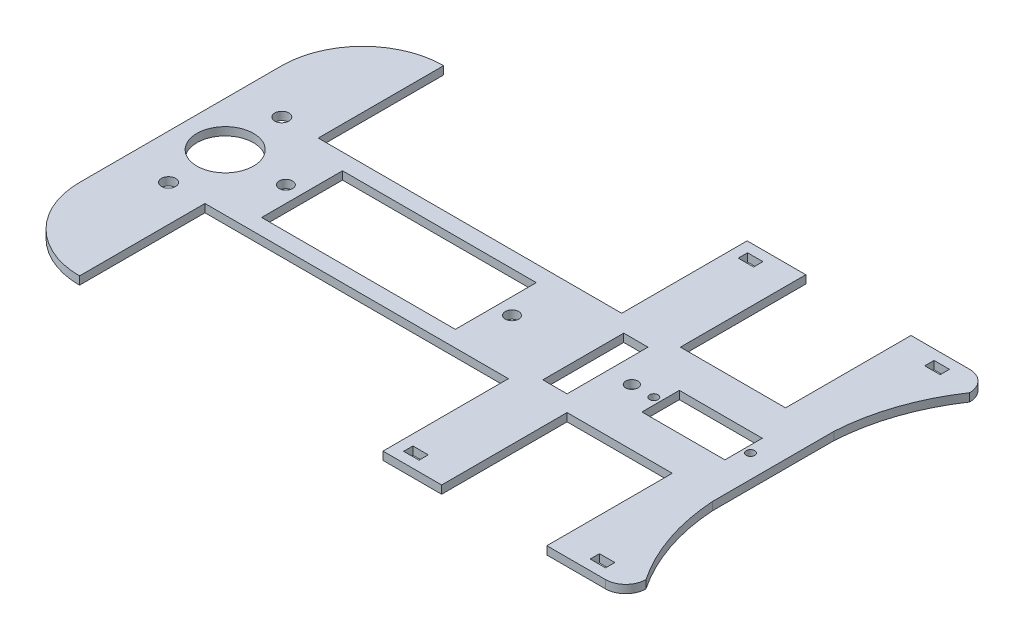
SolidWorks part; units mm, degrees
ref_plane "Front" through (0, 0, 0) normal (0, 0, 1) x (1, 0, 0)
ref_plane "Top" through (0, 0, 0) normal (0, 1, 0) x (1, 0, 0)
ref_plane "Right" through (0, 0, 0) normal (1, 0, 0) x (0, 0, -1)
sketch "Croquis1" plane through (0, 0, 0) normal (0, 1, 0) x (1, 0, 0)
  line L0 (-677.3338, 0) -> (33189.3559, 0) construction
  line L1 (0, -677.3338) -> (0, 33189.3559) construction
  line L2 (-58.4622, -14) -> (-58.4622, 14) construction
  line L3 (-49.4622, 45) -> (-49.4622, 14)
  line L4 (-69.4622, -25) -> (-69.4622, 25)
  line L5 (-49.4622, 14) -> (25.5378, 14)
  line L6 (-677.3338, -25) -> (33189.3559, -25) construction
  line L7 (-677.3338, 25) -> (33189.3559, 25) construction
  line L8 (80.5378, -45) -> (66.0378, -45)
  line L9 (49.1653, -4.625) -> (69.6653, -4.625)
  line L10 (49.1653, -4.625) -> (49.1653, 4.625)
  line L11 (30.0378, -962) -> (30.0378, 49038) construction
  line L12 (28.1378, 40.2) -> (31.9378, 40.2)
  line L13 (28.1378, 40.2) -> (28.1378, 42.5)
  line L14 (28.1378, 42.5) -> (31.9378, 42.5)
  line L15 (31.9378, 40.2) -> (31.9378, 42.5)
  line L16 (28.1378, 40.2) -> (31.9378, 42.5) construction
  line L17 (28.1378, 42.5) -> (31.9378, 40.2) construction
  line L18 (76.1378, -960.85) -> (76.1378, 49039.15) construction
  line L19 (78.0378, 40.2) -> (78.0378, 42.5)
  line L20 (78.0378, 40.2) -> (74.2378, 40.2)
  line L21 (74.2378, 40.2) -> (74.2378, 42.5)
  line L22 (78.0378, 42.5) -> (74.2378, 42.5)
  line L23 (74.2378, -40.2) -> (74.2378, -42.5)
  line L24 (78.0378, -40.2) -> (74.2378, -40.2)
  line L25 (78.0378, -40.2) -> (78.0378, -42.5)
  line L26 (78.0378, -42.5) -> (74.2378, -42.5)
  line L27 (28.1378, -40.2) -> (28.1378, -42.5)
  line L28 (28.1378, -40.2) -> (31.9378, -40.2)
  line L29 (31.9378, -40.2) -> (31.9378, -42.5)
  line L30 (28.1378, -42.5) -> (31.9378, -42.5)
  line L31 (-15.5222, -1000) -> (-15.5222, 49000) construction
  line L32 (37, -1000) -> (37, 49000) construction
  line L33 (49.1653, 4.625) -> (69.6653, 4.625)
  line L34 (77.0378, -15) -> (77.0378, 15)
  line L35 (30.0378, -10) -> (36.0378, -10)
  line L36 (30.0378, -10) -> (30.0378, 10)
  line L37 (30.0378, 10) -> (36.0378, 10)
  line L38 (36.0378, -10) -> (36.0378, 10)
  line L39 (30.0378, -10) -> (36.0378, 10) construction
  line L40 (30.0378, 10) -> (36.0378, -10) construction
  line L41 (69.6653, -4.625) -> (69.6653, 4.625)
  line L42 (49.1653, -4.625) -> (69.6653, 4.625) construction
  line L43 (49.1653, 4.625) -> (69.6653, -4.625) construction
  line L44 (-49.4622, -14) -> (25.5378, -14)
  line L45 (-49.4622, -45) -> (-49.4622, -14)
  line L46 (25.5378, 14) -> (25.5378, 45)
  line L47 (25.5378, 45) -> (40.0378, 45)
  line L48 (80.5378, 45) -> (66.0378, 45)
  line L49 (40.0378, 45) -> (40.0378, 14)
  line L50 (40.0378, 14) -> (66.0378, 14)
  line L51 (66.0378, 14) -> (66.0378, 45)
  line L52 (40.0378, -14) -> (66.0378, -14)
  line L53 (40.0378, -45) -> (40.0378, -14)
  line L54 (25.5378, -45) -> (40.0378, -45)
  line L55 (25.5378, -14) -> (25.5378, -45)
  line L56 (66.0378, -14) -> (66.0378, -45)
  line L58 (-39.4622, -10) -> (8.4178, -10)
  line L59 (-39.4622, -10) -> (-39.4622, 10)
  line L60 (-39.4622, 10) -> (8.4178, 10)
  line L61 (8.4178, -10) -> (8.4178, 10)
  line L62 (-39.4622, -10) -> (8.4178, 10) construction
  line L63 (-39.4622, 10) -> (8.4178, -10) construction
  circle A0 centre (-58.4622, -14) radius 1.75
  circle A1 centre (-58.4622, 14) radius 1.75
  arc A2 (80.5378, -45) -> (85.5378, -40) centre (80.5378, -40) ccw
  circle A3 centre (71.3653, 0) radius 1.05
  circle A4 centre (47.4653, 0) radius 1.05
  arc A5 (85.5378, 40) -> (80.5378, 45) centre (80.5378, 40) ccw
  circle A6 centre (-43.4622, 0) radius 1.65
  circle A7 centre (12.4178, 0) radius 1.65
  arc A8 (-69.4622, 25) -> (-49.4622, 45) centre (-49.4622, 25) cw
  arc A9 (-49.4622, -45) -> (-69.4622, -25) centre (-49.4622, -25) cw
  circle A10 centre (-58.4622, 0) radius 7
  arc A11 (77.0378, 15) -> (85.5378, 40) centre (127.0772, 11.9316) cw
  arc A12 (77.0378, -15) -> (85.5378, -40) centre (127.0772, -11.9316) ccw
  circle A13 centre (42.0378, 0) radius 1.5
  point P4 (0, 0)
  point P13 (-58.4622, 0)
  point P21 (30.0378, 41.35)
  point P42 (59.4153, 0)
  point P45 (77.0378, 0)
  point P47 (76.1378, 42.5)
  point P58 (-15.5222, 0)
  point P66 (33.0378, 0)
  point P75 (70, 15)
  point P86 (52.0378, 25)
  point P96 (-15.5222, 0)
  dimension "D5" = 3.5
  dimension "D6" = 31
  dimension "D12" = 30
  dimension "D14" = 26
  dimension "D15" = 3.3
  dimension "D17" = 14
  dimension "D18" = 31
  dimension "D19" = 20
  dimension "D23" = 5
  dimension "D13" = 75
  dimension "D16" = 55.88
  dimension "D24" = 27.94
  dimension "D27" = 14
  dimension "D33" = 2.1
  dimension "D34" = 5.6725
  dimension "D35" = 2.1
  dimension "D36" = 23.9
  dimension "D39" = 1.7
  dimension "D40" = 6
  dimension "D41" = 47
  dimension "D31" = 4
  dimension "D32" = 3
  dimension "D3" = 28
  dimension "D4" = 11
  dimension "D8" = 3.8
  dimension "D9" = 41
  dimension "D11" = 46.1
  dimension "D20" = 20
  dimension "D21" = 6
  dimension "D22" = 2.3
  dimension "D10" = 146.5
  dimension "D25" = 14.5
  dimension "D26" = 14.5
  dimension "D7" = 130
  dimension "D28" = 30
  dimension "D29" = 3.8
  dimension "D30" = 2.3
  dimension "D37" = 20.5
  dimension "D38" = 9.25
  dimension "D42" = 25
  dimension "D43" = 25
extrude "Saliente-Extruir1" add sketch "Croquis1" along normal blind 2
sketch "Croquis2" [suppressed] plane through (0, 2, 0) normal (0, 1, 0) x (1, 0, 0)
  line L0 (-947.5, 0) -> (49052.5, 0) construction
  line L1 (62.5, -15) -> (62.5, 15) construction
  arc A0 (44.57, -4.8734) -> (44.57, 4.8734) centre (48.07, 0) ccw
  arc A1 (41.57, 3) -> (41.57, -3) centre (41.57, 0) ccw
  arc A2 (41.57, 3) -> (44.57, 4.8734) centre (41.023, 7.2147) ccw
  arc A3 (41.57, -3) -> (44.57, -4.8734) centre (41.023, -7.2147) cw
  point P5 (62.5, 0)
  dimension "D1" = 12
  dimension "D2" = 14.43
  dimension "D3" = 6
  dimension "D4" = 6.5
  dimension "D5" = 4.25
extrude "Cortar-Extruir1" [suppressed] cut sketch "Croquis2" against normal blind 10
